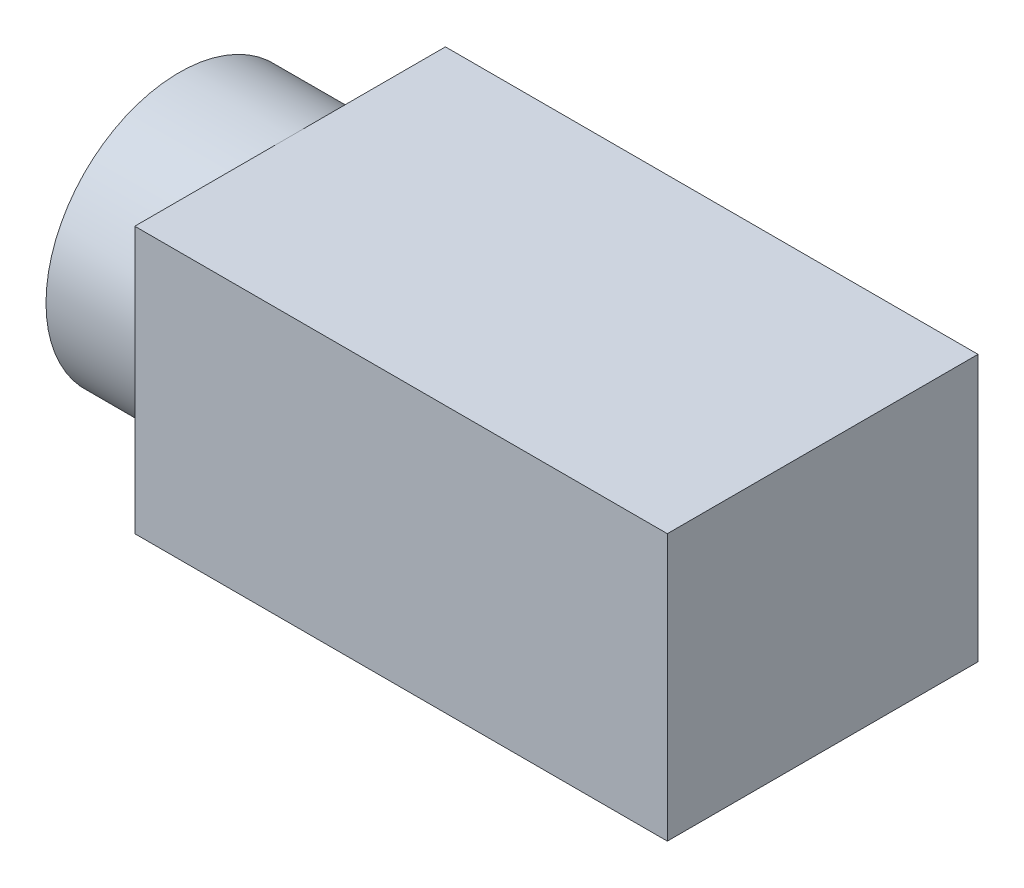
SolidWorks part; units mm, degrees
ref_plane "Front Plane" through (0, 0, 0) normal (0, 0, 1) x (1, 0, 0)
ref_plane "Top Plane" through (0, 0, 0) normal (0, 1, 0) x (1, 0, 0)
ref_plane "Right Plane" through (0, 0, 0) normal (1, 0, 0) x (0, 0, -1)
sketch "Sketch1" plane through (0, 0, 0) normal (0, 0, 1) x (1, 0, 0)
  line L1 (0, 0) -> (12, 0)
  line L2 (0, 0) -> (0, 6)
  line L3 (0, 6) -> (12, 6)
  line L4 (12, 0) -> (12, 6)
  dimension "D1" = 6
  dimension "D2" = 12
extrude "Boss-Extrude1" add sketch "Sketch1" along normal blind 7
sketch "Sketch2" plane through (0, 0, 0) normal (-1, 0, 0) x (0, 0, 1)
  line L0 (7, 6) -> (0, 6) construction
  line L1 (7, 6) -> (7, 0) construction
  circle A0 centre (3.5, 3) radius 3
  point P4 (3.5, 6)
  point P7 (7, 3)
extrude "Boss-Extrude2" add sketch "Sketch2" along normal blind 2.5
sketch "Sketch3" plane through (0, 0, 0) normal (0, -1, 0) x (1, 0, 0)
  line L0 (0, 3.5) -> (12, 3.5) construction
  line L1 (12, 7) -> (12, 0) construction
  line L2 (-2.5, 6.5) -> (-2.5, 0.5) construction
  circle A0 centre (2, 3.5) radius 0.5
  circle A1 centre (9, 3.5) radius 0.5
  dimension "D1" = 1
  dimension "D2" = 4.5
  dimension "D3" = 11.5
extrude "Boss-Extrude3" add sketch "Sketch3" along normal blind 2.1
fillet "Fillet1" radius 0.5 2 edges at (9, -2.1, 3) (2, -2.1, 3)
